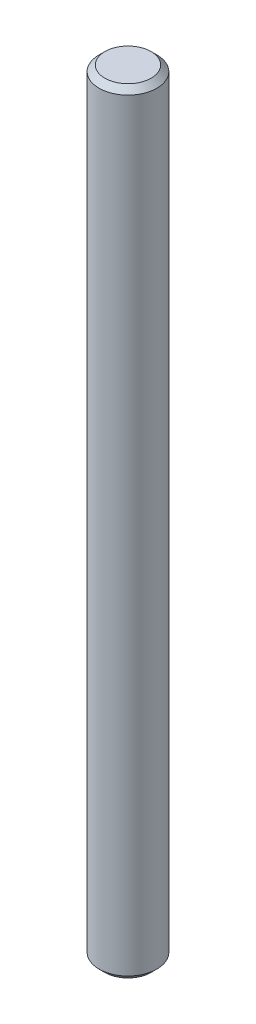
SolidWorks part; units mm, degrees
ref_plane "Front Plane" through (0, 0, 0) normal (0, 0, 1) x (1, 0, 0)
ref_plane "Top Plane" through (0, 0, 0) normal (0, 1, 0) x (1, 0, 0)
ref_plane "Right Plane" through (0, 0, 0) normal (1, 0, 0) x (0, 0, -1)
sketch "Sketch1" plane through (0, 0, 0) normal (0, 1, 0) x (1, 0, 0)
  circle A0 centre (0, 0) radius 2.5
  dimension "D1" = 5
extrude "Boss-Extrude1" add sketch "Sketch1" along normal blind 67
chamfer "Chamfer1" distance 0.5 angle 45 2 edges at (0, 67, 2.5) (0, 0, 2.5)
